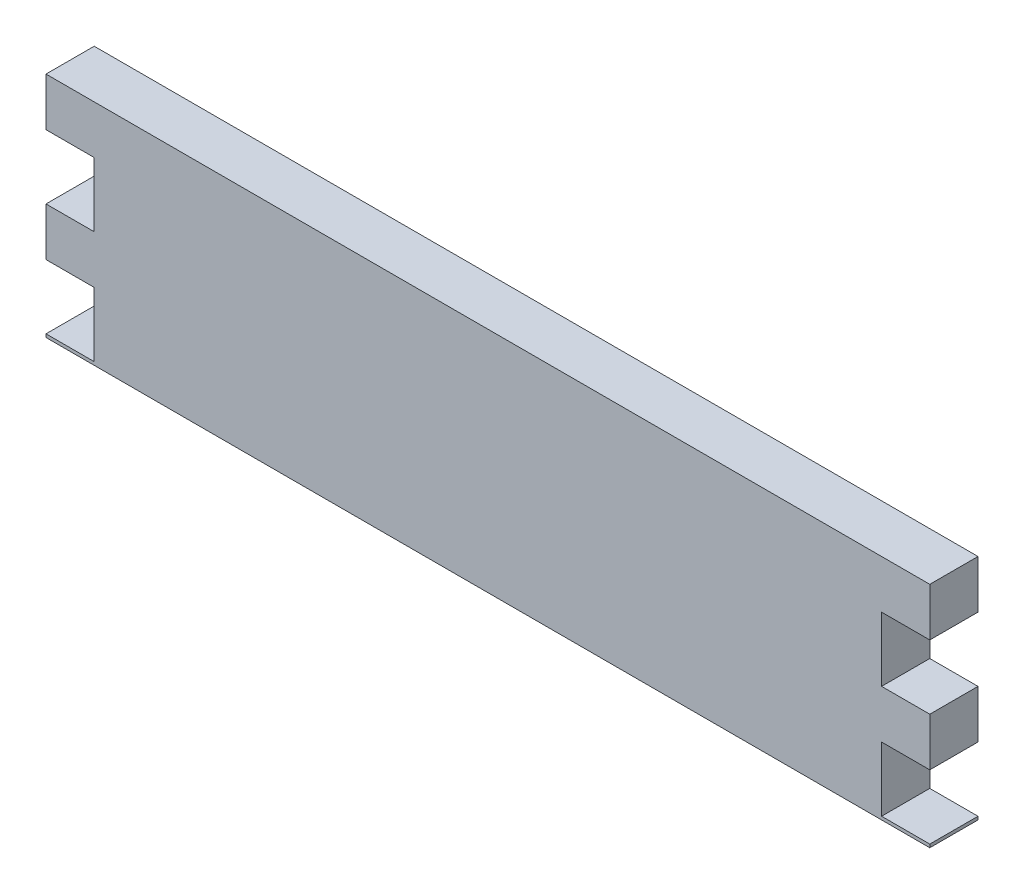
SolidWorks part; units mm, degrees
ref_plane "Plan de face" through (0, 0, 0) normal (0, 0, 1) x (1, 0, 0)
ref_plane "Plan de dessus" through (0, 0, 0) normal (0, 1, 0) x (1, 0, 0)
ref_plane "Plan de droite" through (0, 0, 0) normal (1, 0, 0) x (0, 0, -1)
sketch "Sketch1" plane through (0, 0, 0) normal (0, 0, 1) x (1, 0, 0)
  line L1 (-27.5, -7.1) -> (27.5, -7.1)
  line L2 (-27.5, -7.1) -> (-27.5, 7.1)
  line L3 (-27.5, 7.1) -> (27.5, 7.1)
  line L4 (27.5, -7.1) -> (27.5, 7.1)
  line L5 (-27.5, -7.1) -> (27.5, 7.1) construction
  line L6 (-27.5, 7.1) -> (27.5, -7.1) construction
  point P0 (0, 0)
  dimension "D1" = 55
  dimension "D2" = 14.2
extrude "Boss-Extrude1" add sketch "Sketch1" along normal blind 3
sketch "Sketch3" plane through (0, 0, 3) normal (0, 0, 1) x (1, 0, 0)
  line L0 (-27.5, 7.1) -> (-27.5, -7.1) construction
  line L1 (-27.5, 4.1) -> (-24.5, 4.1)
  line L2 (-27.5, 4.1) -> (-27.5, 0.1)
  line L3 (-27.5, 0.1) -> (-24.5, 0.1)
  line L4 (-24.5, 4.1) -> (-24.5, 0.1)
  line L5 (27.5, 7.1) -> (-27.5, 7.1) construction
  line L7 (-27.5, -2.9) -> (-24.5, -2.9)
  line L8 (-27.5, -2.9) -> (-27.5, -6.9)
  line L9 (-27.5, -6.9) -> (-24.5, -6.9)
  line L10 (-24.5, -2.9) -> (-24.5, -6.9)
  dimension "D1" = 3
  dimension "D2" = 3
  dimension "D3" = 4
  dimension "D4" = 4
  dimension "D5" = 3
  dimension "D6" = 3
extrude "Cut-Extrude1" cut sketch "Sketch3" against normal blind 10
sketch "Sketch4" plane through (0, 0, 3) normal (0, 0, 1) x (1, 0, 0)
  line L0 (27.5, -7.1) -> (27.5, 7.1) construction
  line L1 (27.5, 4.1) -> (24.5, 4.1)
  line L2 (27.5, 4.1) -> (27.5, 0.1)
  line L3 (27.5, 0.1) -> (24.5, 0.1)
  line L4 (24.5, 4.1) -> (24.5, 0.1)
  line L5 (27.5, 7.1) -> (-27.5, 7.1) construction
  line L6 (-27.5, -7.1) -> (27.5, -7.1) construction
  line L7 (27.5, -2.9) -> (24.5, -2.9)
  line L8 (27.5, -2.9) -> (27.5, -6.9)
  line L9 (27.5, -6.9) -> (24.5, -6.9)
  line L10 (24.5, -2.9) -> (24.5, -6.9)
  dimension "D1" = 3
  dimension "D2" = 3
  dimension "D3" = 4
  dimension "D4" = 4
  dimension "D5" = 3
  dimension "D6" = 3
extrude "Cut-Extrude2" cut sketch "Sketch4" against normal blind 10
